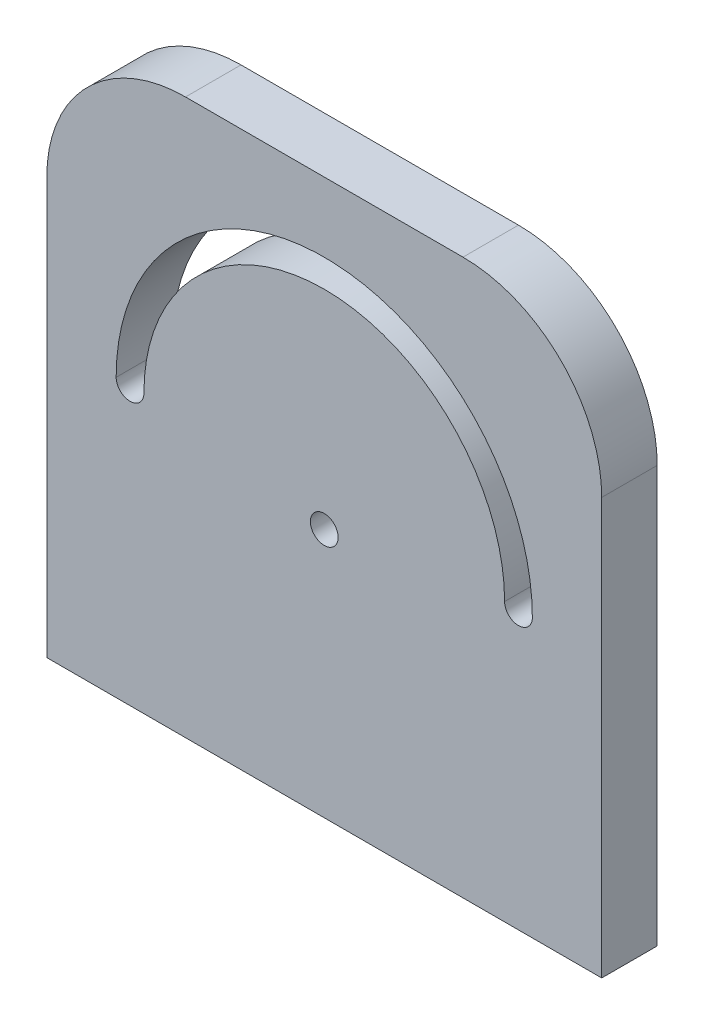
SolidWorks part; units mm, degrees
ref_plane "Front Plane" through (0, 0, 0) normal (0, 0, 1) x (1, 0, 0)
ref_plane "Top Plane" through (0, 0, 0) normal (0, 1, 0) x (1, 0, 0)
ref_plane "Right Plane" through (0, 0, 0) normal (1, 0, 0) x (0, 0, -1)
sketch "Sketch1" plane through (0, 0, 0) normal (0, 0, 1) x (1, 0, 0)
  line L1 (50, -50) -> (-50, -50)
  line L2 (50, -50) -> (50, 50)
  line L3 (50, 50) -> (-50, 50)
  line L4 (-50, -50) -> (-50, 50)
  line L5 (50, -50) -> (-50, 50) construction
  line L6 (50, 50) -> (-50, -50) construction
  point P0 (0, 0)
  dimension "D1" = 100
  dimension "D2" = 100
extrude "Boss-Extrude1" add sketch "Sketch1" along normal blind 10
sketch "Sketch2" plane through (0, 0, 0) normal (0, 0, -1) x (-1, 0, 0)
  line L0 (0, 50) -> (0, -50) construction
  line L1 (-50, 50) -> (50, 50) construction
  line L2 (50, -50) -> (-50, -50) construction
  line L3 (-47.8648, 35) -> (50, 35) construction
  line L4 (50, 50) -> (50, -50) construction
  line L5 (-35, 50) -> (-35, -50) construction
  line L6 (35, 50) -> (35, -50) construction
  line L7 (-50, -50) -> (-50, 50) construction
  circle A0 centre (0, -5) radius 2.5
  arc A1 (-35, 0) -> (35, 0) centre (0, 0) cw construction
  arc A2 (37.5, 0) -> (-37.5, 0) centre (0, 0) ccw
  arc A3 (32.5, 0) -> (-32.5, 0) centre (0, 0) ccw
  arc A4 (32.5, 0) -> (37.5, 0) centre (35, 0) ccw
  arc A5 (-37.5, 0) -> (-32.5, 0) centre (-35, 0) ccw
  point P22 (0, 35)
  dimension "D1" = 5
  dimension "D6" = 5
  dimension "D2" = 45
  dimension "D3" = 15
  dimension "D4" = 15
  dimension "D5" = 15
extrude "Cut-Extrude1" cut sketch "Sketch2" against normal up to next
sketch "Sketch3" plane through (0, -50, 0) normal (0, -1, 0) x (1, 0, 0)
  line L0 (-50, 5) -> (50, 5) construction
  line L1 (-50, 10) -> (-50, 0) construction
  line L2 (50, 10) -> (50, 0) construction
  circle A0 centre (-35, 5) radius 2.5
  circle A1 centre (0, 5) radius 2.5
  circle A2 centre (35, 5) radius 2.5
  dimension "D3" = 5
  dimension "D1" = 15
  dimension "D2" = 15
extrude "Cut-Extrude2" cut sketch "Sketch3" against normal blind 20
fillet "Fillet2" radius 25 1 edges at (-50, 50, 5)
fillet "Fillet3" radius 25 1 edges at (50, 50, 5)
